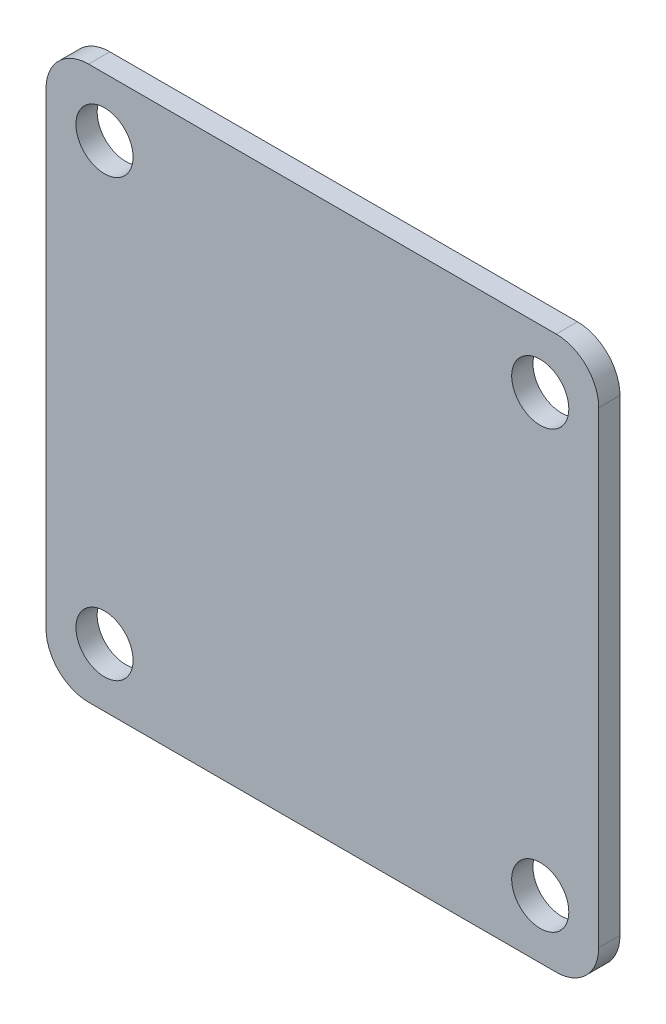
SolidWorks part; units mm, degrees
ref_plane "Front Plane" through (0, 0, 0) normal (0, 0, 1) x (1, 0, 0)
ref_plane "Top Plane" through (0, 0, 0) normal (0, 1, 0) x (1, 0, 0)
ref_plane "Right Plane" through (0, 0, 0) normal (1, 0, 0) x (0, 0, -1)
sketch "Sketch1" plane through (0, 0, 0) normal (0, 0, 1) x (1, 0, 0)
  line L0 (-82.55, 0) -> (82.55, 0) construction
  line L1 (-82.55, -82.55) -> (82.55, -82.55)
  line L2 (-82.55, -82.55) -> (-82.55, 82.55)
  line L3 (-82.55, 82.55) -> (82.55, 82.55)
  line L4 (82.55, -82.55) -> (82.55, 82.55)
  circle A0 centre (-65.0875, -65.0875) radius 8.5328
  circle A1 centre (-65.0875, 65.0875) radius 8.5328
  circle A2 centre (65.0875, 65.0875) radius 8.5328
  circle A3 centre (65.0875, -65.0875) radius 8.5328
  circle A4 centre (-65.0875, -65.0875) radius 8.5328 construction
  circle A5 centre (-65.0875, 65.0875) radius 8.5328 construction
  circle A6 centre (65.0875, 65.0875) radius 8.5328 construction
  circle A7 centre (65.0875, -65.0875) radius 8.5328 construction
  dimension "D1" = 165.1
extrude "Extrude1" add sketch "Sketch1" along normal blind 6.35
fillet "Fillet1" radius 12.7 4 edges at (-82.55, 82.55, 3.175) (-82.55, -82.55, 3.175) (82.55, -82.55, 3.175) (82.55, 82.55, 3.175)
